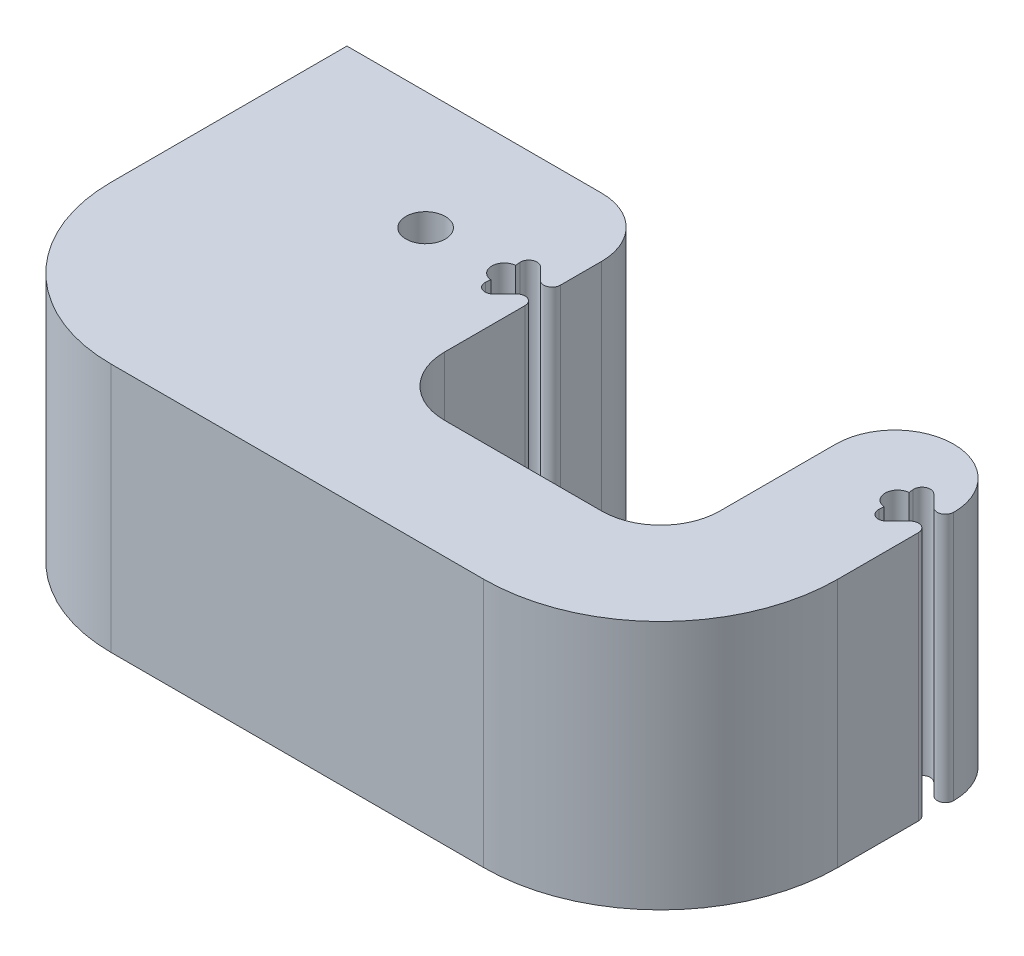
SolidWorks part; units mm, degrees
material "6061 Alloy"
ref_plane "Front Plane" through (0, 0, 0) normal (0, 0, 1) x (1, 0, 0)
ref_plane "Top Plane" through (0, 0, 0) normal (0, 1, 0) x (1, 0, 0)
ref_plane "Right Plane" through (0, 0, 0) normal (1, 0, 0) x (0, 0, -1)
sketch "Sketch1" plane through (0, 0, 0) normal (0, 1, 0) x (1, 0, 0)
  line L0 (0, 0) -> (-4, 0) construction
  line L1 (-4, 0) -> (-4.0553, 0.6326) construction
  line L2 (-4.0553, 0.6326) -> (-4.0758, 0.8669)
  line L3 (-3.3615, 1.2) -> (-2.7615, 0.6)
  line L4 (-4, 0) -> (-3.0808, 0.9192) construction
  line L5 (-6.465, 0.8965) -> (-2.465, 0.8965) construction
  line L6 (-4.0553, -0.6326) -> (-4.0758, -0.8669)
  line L7 (-3.3615, -1.2) -> (-2.7615, -0.6)
  line L8 (-2.0456, 0.8965) -> (-2.0456, 3)
  line L12 (-5.0456, 6) -> (-18, 6)
  line L13 (-18, 6) -> (-18, -6)
  line L16 (-2.0456, -0.8965) -> (-2.0456, -5)
  line L18 (0.9544, -8) -> (8.9544, -8)
  line L19 (-10, -14) -> (8.9544, -14)
  line L28 (16.6385, -1.2) -> (17.2385, -0.6)
  line L29 (15.9447, -0.6326) -> (15.9242, -0.8669)
  line L30 (15.9447, 0.6326) -> (15.9242, 0.8669)
  line L31 (16.6385, 1.2) -> (17.2385, 0.6)
  line L32 (-2.7615, -0.6) -> (17.2385, -0.6) construction
  line L37 (11.9544, -5) -> (11.9544, 0.8965)
  line L41 (17.9544, -0.8965) -> (17.9544, -5)
  line L42 (17.535, 0.8965) -> (14.9544, 0.8965) construction
  circle A0 centre (-4, 0) radius 0.635 construction
  arc A1 (-4.0758, 0.8669) -> (-3.3615, 1.2) centre (-3.6581, 0.9035) cw
  arc A2 (-2.7615, 0.6) -> (-2.0456, 0.8965) centre (-2.465, 0.8965) ccw
  arc A4 (-4.0553, 0.6326) -> (-4.0553, -0.6326) centre (-4, 0) ccw
  arc A5 (-4.0758, -0.8669) -> (-3.3615, -1.2) centre (-3.6581, -0.9035) ccw
  arc A6 (-2.7615, -0.6) -> (-2.0456, -0.8965) centre (-2.465, -0.8965) cw
  arc A63 (-2.0456, 3) -> (-5.0456, 6) centre (-5.0456, 3) ccw
  circle A65 centre (-8, 0) radius 1
  arc A66 (-2.0456, -5) -> (0.9544, -8) centre (0.9544, -5) ccw
  arc A67 (-18, -6) -> (-10, -14) centre (-10, -6) ccw
  arc A77 (17.2385, -0.6) -> (17.9544, -0.8965) centre (17.535, -0.8965) cw
  arc A78 (15.9242, -0.8669) -> (16.6385, -1.2) centre (16.3419, -0.9035) ccw
  arc A79 (15.9447, 0.6326) -> (15.9447, -0.6326) centre (16, 0) ccw
  arc A80 (15.9242, 0.8669) -> (16.6385, 1.2) centre (16.3419, 0.9035) cw
  arc A81 (17.2385, 0.6) -> (17.9544, 0.8965) centre (17.535, 0.8965) ccw
  arc A82 (8.9544, -8) -> (11.9544, -5) centre (8.9544, -5) ccw
  arc A83 (11.9544, 0.8965) -> (17.9544, 0.8965) centre (14.9544, 0.8965) cw
  arc A85 (8.9544, -14) -> (17.9544, -5) centre (8.9544, -5) ccw
  point P0 (0, 0)
  dimension "D1" = 1.27
  dimension "D16" = 20
  dimension "D13" = 12
  dimension "D8" = 6
  dimension "D15" = 2
  dimension "D10" = 18
  dimension "D11" = 2
  dimension "D9" = 3
  dimension "D14" = 8
  dimension "D2" = 4
  dimension "D3" = 95
  dimension "D4" = 45
  dimension "D5" = 1.2
  dimension "D6" = 1.3
  dimension "D7" = 0.6
  dimension "D12" = 10
extrude "Boss-Extrude1" add sketch "Sketch1" along normal blind 12.7
sketch "Sketch2" plane through (-18, 0, 0) normal (-1, 0, 0) x (0, 0, 1)
  line L0 (-6, 12.7) -> (6, 0) construction
  circle A0 centre (0, 6.35) radius 4
  dimension "D1" = 8
extrude "Cut-Extrude1" cut sketch "Sketch2" against normal blind 10
